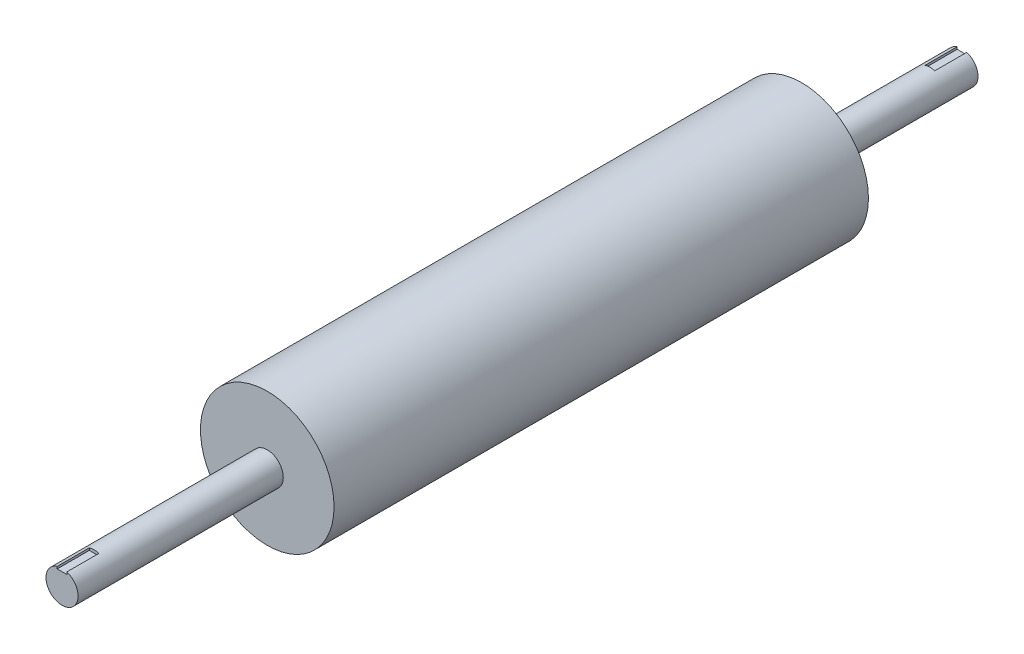
SolidWorks part; units mm, degrees
material "AISI 1020 Steel, Cold Rolled"
ref_plane "Front Plane" through (0, 0, 0) normal (0, 0, 1) x (1, 0, 0)
ref_plane "Top Plane" through (0, 0, 0) normal (0, 1, 0) x (1, 0, 0)
ref_plane "Right Plane" through (0, 0, 0) normal (1, 0, 0) x (0, 0, -1)
sketch "Sketch2" plane through (0, 0, 0) normal (0, 0, 1) x (1, 0, 0)
  line L0 (0, 125) -> (0, 209.7943) construction
  line L1 (-125, 0) -> (-247.6393, 0) construction
  line L2 (-88.3883, -88.3883) -> (-164.03, -164.03) construction
  circle A0 centre (0, 0) radius 125
  point P6 (0, 167.3971)
  dimension "D1" = 250
extrude "Boss-Extrude1" add sketch "Sketch2" along normal blind 1000
sketch "Sketch7" plane through (0, 0, 1000) normal (0, 0, 1) x (1, 0, 0)
  circle A0 centre (0, 0) radius 30
  dimension "D1" = 60
extrude "Boss-Extrude3" add sketch "Sketch7" along normal blind 384.03
sketch "Sketch8" plane through (0, 0, 0) normal (0, 0, -1) x (-1, 0, 0)
  circle A0 centre (0, 0) radius 30
  dimension "D1" = 60
extrude "Boss-Extrude4" add sketch "Sketch8" along normal blind 300
sketch "Sketch18" plane through (0, 0, 1384.03) normal (0, 0, 1) x (1, 0, 0)
  line L1 (-9, 24.5) -> (9, 24.5)
  line L2 (-9, 24.5) -> (-9, 35.5)
  line L3 (-9, 35.5) -> (9, 35.5)
  line L4 (9, 24.5) -> (9, 35.5)
  line L5 (-9, 24.5) -> (9, 35.5) construction
  line L6 (-9, 35.5) -> (9, 24.5) construction
  circle A0 centre (0, 0) radius 30 construction
  circle A1 centre (0, 0) radius 30 construction
  point P0 (0, 30)
  dimension "D1" = 5.5
  dimension "D2" = 18
extrude "Cut-Extrude2" cut sketch "Sketch18" against normal blind 60
sketch "Sketch19" plane through (0, 0, -300) normal (0, 0, -1) x (-1, 0, 0)
  line L1 (-9, 24.5) -> (9, 24.5)
  line L2 (-9, 24.5) -> (-9, 35.5)
  line L3 (-9, 35.5) -> (9, 35.5)
  line L4 (9, 24.5) -> (9, 35.5)
  line L5 (-9, 24.5) -> (9, 35.5) construction
  line L6 (-9, 35.5) -> (9, 24.5) construction
  circle A0 centre (0, 0) radius 30 construction
  circle A1 centre (0, 0) radius 30 construction
  point P0 (0, 30)
  dimension "D1" = 18
  dimension "D2" = 11
extrude "Cut-Extrude3" cut sketch "Sketch19" against normal blind 60
